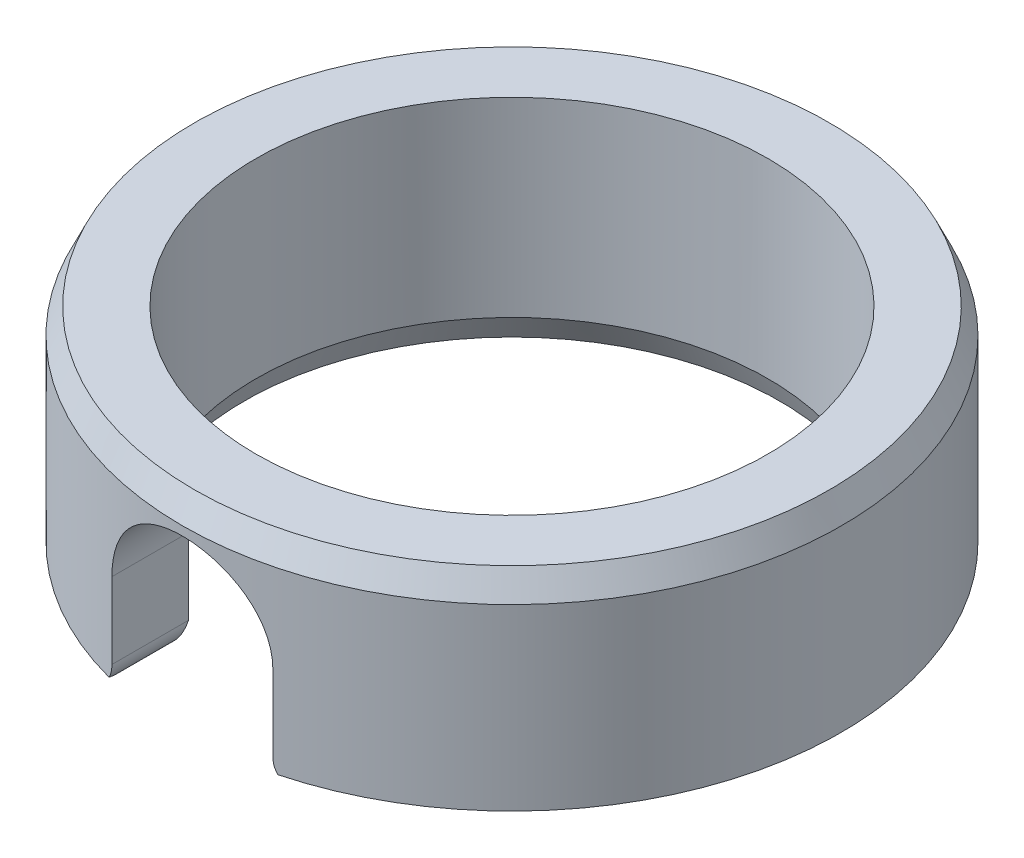
SolidWorks part; units mm, degrees
ref_plane "Front Plane" through (0, 0, 0) normal (0, 0, 1) x (1, 0, 0)
ref_plane "Top Plane" through (0, 0, 0) normal (0, 1, 0) x (1, 0, 0)
ref_plane "Right Plane" through (0, 0, 0) normal (1, 0, 0) x (0, 0, -1)
sketch "Sketch1" plane through (0, 0, 0) normal (0, 1, 0) x (1, 0, 0)
  circle A0 centre (0, 0) radius 13
  circle A1 centre (0, 0) radius 10.1
  dimension "D1" = 20.2
  dimension "D2" = 26
extrude "Boss-Extrude1" add sketch "Sketch1" along normal blind 8.5222
sketch "Sketch2" plane through (0, 0, 0) normal (0, 0, 1) x (1, 0, 0)
  line L0 (-3.175, 4) -> (-3.175, 0)
  line L1 (-3.175, 0) -> (3.175, 0)
  line L2 (-13, 0) -> (13, 0) construction
  line L3 (3.175, 0) -> (3.175, 4)
  arc A0 (3.175, 4) -> (-3.175, 4) centre (0, 4) ccw
  dimension "D1" = 6.35
  dimension "D2" = 4
extrude "Cut-Extrude1" cut sketch "Sketch2" along normal through all
chamfer "Chamfer1" distance 1 angle 25 3 edges at (0, 0, -10.1) (0, 0, -13) (0, 8.5222, 13)
fillet "Fillet2" radius 1 2 edges at (3.175, 0, 10.8252) (-3.175, 0, 10.8252)
